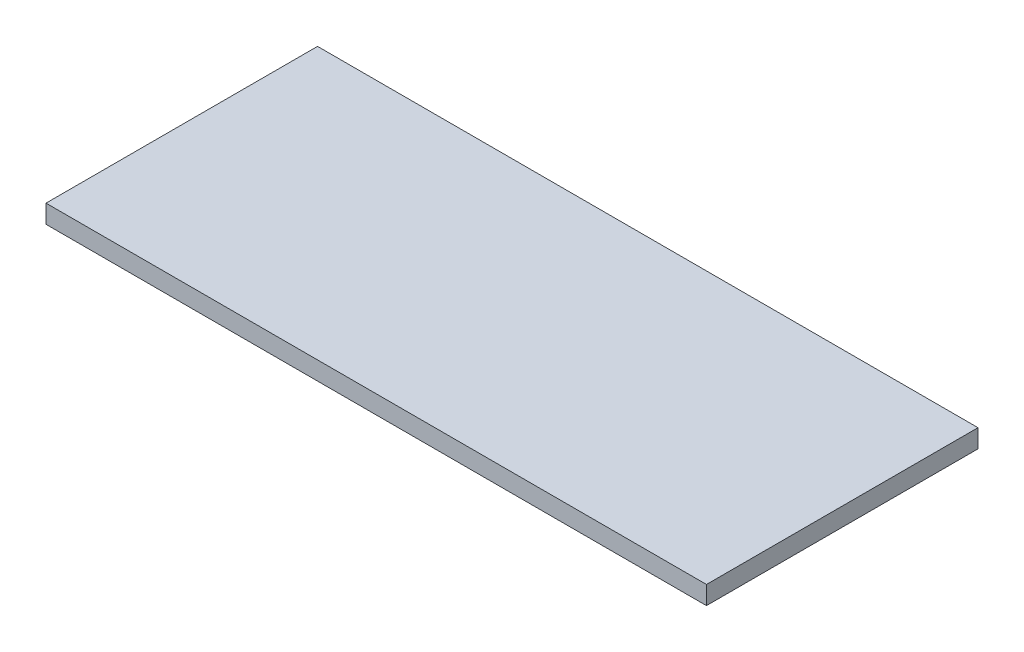
SolidWorks part; units mm, degrees
ref_plane "Front Plane" through (0, 0, 0) normal (0, 0, 1) x (1, 0, 0)
ref_plane "Top Plane" through (0, 0, 0) normal (0, 1, 0) x (1, 0, 0)
ref_plane "Right Plane" through (0, 0, 0) normal (1, 0, 0) x (0, 0, -1)
sketch "Sketch1" plane through (0, 0, 0) normal (0, 1, 0) x (1, 0, 0)
  line L1 (-228.6, 93.98) -> (228.6, 93.98)
  line L2 (-228.6, 93.98) -> (-228.6, -93.98)
  line L3 (-228.6, -93.98) -> (228.6, -93.98)
  line L4 (228.6, 93.98) -> (228.6, -93.98)
  line L5 (-228.6, 93.98) -> (228.6, -93.98) construction
  line L6 (-228.6, -93.98) -> (228.6, 93.98) construction
  point P0 (0, 0)
  dimension "D1" = 187.96
  dimension "D2" = 457.2
extrude "Boss-Extrude1" add sketch "Sketch1" along normal blind 12.7
